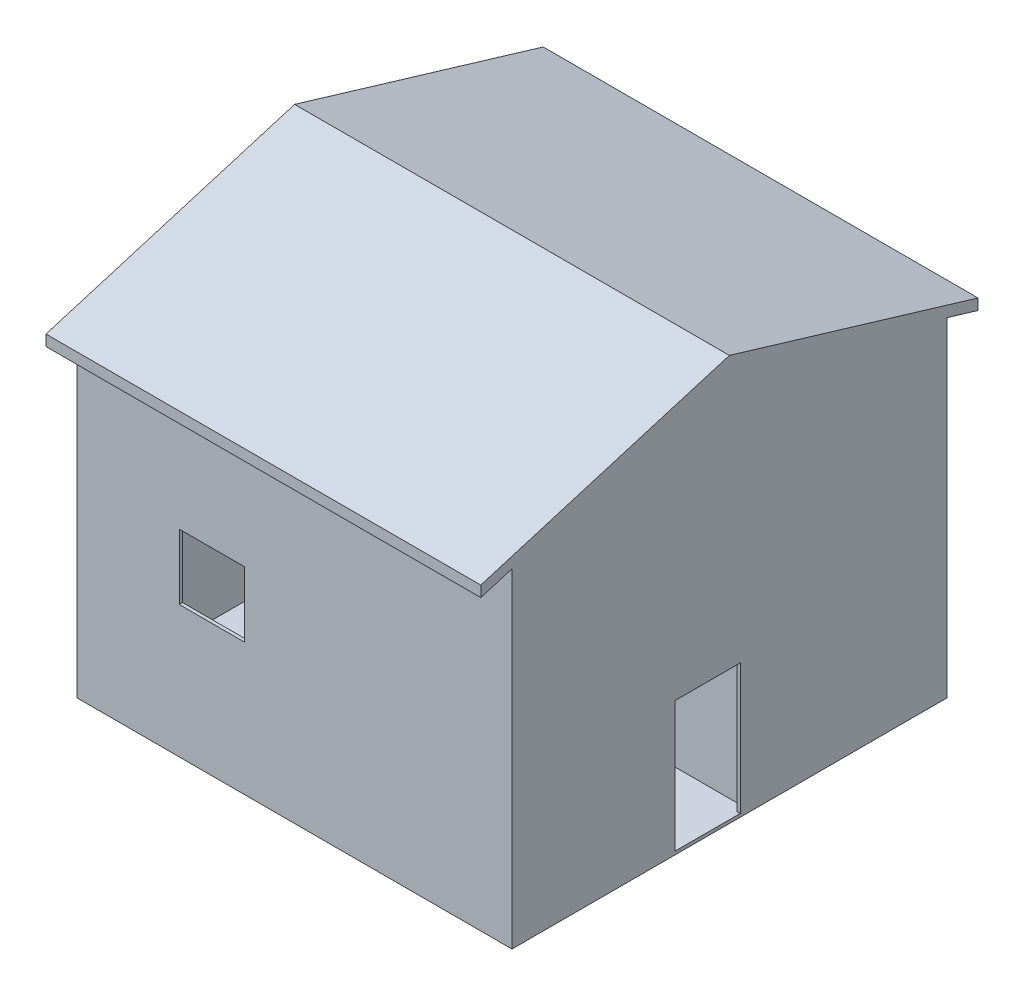
SolidWorks part; units mm, degrees
material "純金"
ref_plane "前基準面" through (0, 0, 0) normal (0, 0, 1) x (1, 0, 0)
ref_plane "上基準面" through (0, 0, 0) normal (0, 1, 0) x (1, 0, 0)
ref_plane "右基準面" through (0, 0, 0) normal (1, 0, 0) x (0, 0, -1)
ref_plane "平面1" through (98.5, 0, 0) normal (-1, 0, 0) x (0, -1, 0)
sketch "草圖1" plane through (98.5, 0, 0) normal (-1, 0, 0) x (0, -1, 0)
  line L0 (-1.5, -5) -> (-151.5, -5)
  line L1 (-151.5, -5) -> (-151.5, -8.5)
  line L2 (-151.5, -8.5) -> (-1.5, -8.5)
  line L3 (-1.5, -8.5) -> (-1.5, -5)
extrude "填料-伸長1" add sketch "草圖1" against normal blind 1.5
sketch "草圖2" plane through (0, 0, -8.5) normal (0, 0, -1) x (-1, 0, 0)
  line L0 (21.1717, 1.5) -> (-100, 1.5)
  line L1 (-100, 1.5) -> (-100, 151.5)
  line L2 (-100, 151.5) -> (21.1717, 151.5)
  line L3 (21.1717, 151.5) -> (21.1717, 1.5)
extrude "填料-伸長2" add sketch "草圖2" along normal blind 91.5
sketch "草圖3" plane through (0, 0, -5) normal (0, 0, 1) x (1, 0, 0)
  line L0 (98.5, 61.5) -> (98.5, 151.5)
  line L1 (98.5, 151.5) -> (100, 151.5)
  line L2 (100, 151.5) -> (100, 61.5)
  line L3 (100, 61.5) -> (98.5, 61.5)
extrude "填料-伸長3" add sketch "草圖3" along normal blind 30
sketch "草圖4" plane through (-21.1717, 0, 0) normal (-1, 0, 0) x (0, 0, 1)
  line L0 (-100, 1.5) -> (-100, 151.5)
  line L1 (-100, 151.5) -> (-8.5, 151.5)
  line L2 (-8.5, 151.5) -> (-8.5, 61.5)
  line L3 (-8.5, 61.5) -> (-10, 61.5)
  line L4 (-10, 61.5) -> (-10, 1.5)
  line L5 (-10, 1.5) -> (-100, 1.5)
extrude "填料-伸長4" add sketch "草圖4" along normal blind 30
sketch "草圖5" plane through (0, 1.5, 0) normal (0, -1, 0) x (1, 0, 0)
  line L0 (-51.1717, 25) -> (100, 25)
  line L1 (100, 25) -> (100, -100)
  line L2 (100, -100) -> (-51.1717, -100)
  line L3 (-51.1717, -100) -> (-51.1717, 25)
extrude "填料-伸長5" add sketch "草圖5" along normal blind 1.5
sketch "草圖6" plane through (-51.1717, 0, 0) normal (-1, 0, 0) x (0, 0, 1)
  line L0 (25, 0) -> (-100, 0)
  line L1 (-100, 0) -> (-100, 151.5)
  line L2 (-100, 151.5) -> (25, 151.5)
  line L3 (25, 151.5) -> (25, 0)
extrude "填料-伸長6" add sketch "草圖6" along normal blind 48.8283
sketch "草圖7" plane through (0, 0, 25) normal (0, 0, 1) x (1, 0, 0)
  line L0 (100, 0) -> (-100, 0)
  line L1 (-100, 0) -> (-100, 151.5)
  line L2 (-100, 151.5) -> (100, 151.5)
  line L3 (100, 151.5) -> (100, 0)
extrude "填料-伸長7" add sketch "草圖7" along normal blind 75
sketch "草圖8" plane through (0, 0, 25) normal (0, 0, -1) x (-1, 0, 0)
  line L0 (-23.5, 151.5) -> (-23.5, 1.5)
  line L1 (-23.5, 1.5) -> (51.1717, 1.5)
  line L2 (51.1717, 1.5) -> (51.1717, 151.5)
  line L3 (51.1717, 151.5) -> (-23.5, 151.5)
extrude "除料-伸長1" cut sketch "草圖8" against normal blind 53.5
sketch "草圖9" plane through (0, 0, -10) normal (0, 0, 1) x (1, 0, 0)
  line L0 (-21.1717, 1.5) -> (-21.1717, 151.5)
  line L1 (-21.1717, 151.5) -> (-51.1717, 151.5)
  line L2 (-51.1717, 151.5) -> (-51.1717, 1.5)
  line L3 (-51.1717, 1.5) -> (-21.1717, 1.5)
extrude "除料-伸長2" cut sketch "草圖9" against normal blind 59.25
sketch "草圖10" plane through (-21.1717, 0, 0) normal (-1, 0, 0) x (0, 0, 1)
  line L0 (-69.25, 151.5) -> (-69.25, 1.5)
  line L1 (-69.25, 1.5) -> (-10, 1.5)
  line L2 (-10, 1.5) -> (-10, 151.5)
  line L3 (-10, 151.5) -> (-69.25, 151.5)
extrude "除料-伸長3" cut sketch "草圖10" against normal blind 42.6717
sketch "草圖11" plane through (23.5, 0, 0) normal (-1, 0, 0) x (0, 0, 1)
  line L0 (78.5, 61.5) -> (48.5, 61.5)
  line L1 (48.5, 61.5) -> (48.5, 1.5)
  line L2 (48.5, 1.5) -> (78.5, 1.5)
  line L3 (78.5, 1.5) -> (78.5, 61.5)
extrude "除料-伸長4" cut sketch "草圖11" against normal blind 1.5
sketch "草圖12" plane through (21.5, 0, 0) normal (-1, 0, 0) x (0, 0, 1)
  line L0 (-69.25, 61.5) -> (-69.25, 1.5)
  line L1 (-69.25, 1.5) -> (-39.25, 1.5)
  line L2 (-39.25, 1.5) -> (-39.25, 61.5)
  line L3 (-39.25, 61.5) -> (-69.25, 61.5)
extrude "除料-伸長5" cut sketch "草圖12" against normal blind 1.5
sketch "草圖13" plane through (-51.1717, 0, 0) normal (1, 0, 0) x (0, 0, -1)
  line L0 (-78.5, 151.5) -> (-78.5, 1.5)
  line L1 (-78.5, 1.5) -> (8.5, 1.5)
  line L2 (8.5, 1.5) -> (8.5, 151.5)
  line L3 (8.5, 151.5) -> (-78.5, 151.5)
extrude "除料-伸長6" cut sketch "草圖13" against normal blind 47.3283
sketch "草圖14" plane through (-51.1717, 0, 0) normal (1, 0, 0) x (0, 0, -1)
  line L0 (69.25, 1.5) -> (69.25, 151.5)
  line L1 (69.25, 151.5) -> (10, 151.5)
  line L2 (10, 151.5) -> (10, 1.5)
  line L3 (10, 1.5) -> (69.25, 1.5)
extrude "除料-伸長7" cut sketch "草圖14" against normal blind 47.3283
sketch "草圖15" plane through (0, 0, -69.25) normal (0, 0, 1) x (1, 0, 0)
  line L0 (-98.5, 1.5) -> (21.5, 1.5)
  line L1 (21.5, 1.5) -> (21.5, 151.5)
  line L2 (21.5, 151.5) -> (-98.5, 151.5)
  line L3 (-98.5, 151.5) -> (-98.5, 1.5)
extrude "除料-伸長8" cut sketch "草圖15" against normal blind 29.25
sketch "草圖16" plane through (23, 0, 0) normal (-1, 0, 0) x (0, 0, 1)
  line L0 (-98.5, 1.5) -> (-10, 1.5)
  line L1 (-10, 1.5) -> (-10, 151.5)
  line L2 (-10, 151.5) -> (-98.5, 151.5)
  line L3 (-98.5, 151.5) -> (-98.5, 1.5)
extrude "除料-伸長9" cut sketch "草圖16" against normal blind 75.5
sketch "草圖17" plane through (0, 0, 78.5) normal (0, 0, -1) x (-1, 0, 0)
  line L0 (98.5, 151.5) -> (-23.5, 151.5)
  line L1 (-23.5, 151.5) -> (-23.5, 1.5)
  line L2 (-23.5, 1.5) -> (98.5, 1.5)
  line L3 (98.5, 1.5) -> (98.5, 151.5)
extrude "除料-伸長10" cut sketch "草圖17" against normal blind 20
sketch "草圖18" plane through (25, 0, 0) normal (-1, 0, 0) x (0, 0, 1)
  line L0 (98.5, 151.5) -> (48.5, 151.5)
  line L1 (48.5, 151.5) -> (48.5, 1.5)
  line L2 (48.5, 1.5) -> (98.5, 1.5)
  line L3 (98.5, 1.5) -> (98.5, 151.5)
extrude "除料-伸長11" cut sketch "草圖18" against normal blind 73.5
sketch "草圖19" plane through (0, 0, 48.5) normal (0, 0, 1) x (1, 0, 0)
  line L0 (25, 1.5) -> (98.5, 1.5)
  line L1 (98.5, 1.5) -> (98.5, 151.5)
  line L2 (98.5, 151.5) -> (25, 151.5)
  line L3 (25, 151.5) -> (25, 1.5)
extrude "除料-伸長12" cut sketch "草圖19" against normal blind 18.5
sketch "草圖20" plane through (0, 0, 25) normal (0, 0, -1) x (-1, 0, 0)
  line L0 (-98.5, 1.5) -> (-23.5, 1.5)
  line L1 (-23.5, 1.5) -> (-23.5, 151.5)
  line L2 (-23.5, 151.5) -> (-98.5, 151.5)
  line L3 (-98.5, 151.5) -> (-98.5, 1.5)
extrude "除料-伸長13" cut sketch "草圖20" against normal blind 3.5
sketch "草圖21" plane through (0, 0, -100) normal (0, 0, -1) x (-1, 0, 0)
  line L0 (-67.804, 45.1558) -> (-37.804, 45.1558)
  line L1 (-37.804, 45.1558) -> (-37.804, 75.1558)
  line L2 (-37.804, 75.1558) -> (-67.804, 75.1558)
  line L3 (-67.804, 75.1558) -> (-67.804, 45.1558)
extrude "除料-伸長14" cut sketch "草圖21" against normal up to next
sketch "草圖22" plane through (0, 0, -100) normal (0, 0, -1) x (-1, 0, 0)
  line L0 (51.2266, 45.5945) -> (51.2266, 75.5945)
  line L1 (51.2266, 75.5945) -> (21.2266, 75.5945)
  line L2 (21.2266, 75.5945) -> (21.2266, 45.5945)
  line L3 (21.2266, 45.5945) -> (51.2266, 45.5945)
extrude "除料-伸長15" cut sketch "草圖22" against normal up to next
sketch "草圖23" plane through (0, 0, 100) normal (0, 0, 1) x (1, 0, 0)
  line L0 (-53.0614, 60.75) -> (-23.0614, 60.75)
  line L1 (-23.0614, 60.75) -> (-23.0614, 90.75)
  line L2 (-23.0614, 90.75) -> (-53.0614, 90.75)
  line L3 (-53.0614, 90.75) -> (-53.0614, 60.75)
extrude "除料-伸長16" cut sketch "草圖23" against normal up to next
sketch "草圖24" plane through (0, 1.5, 0) normal (0, 1, 0) x (1, 0, 0)
  line L1 (98.5, 8.5) -> (98.5, 5) construction
  line L3 (100, 5) -> (98.5, 5) construction
  circle A0 centre (98, 4.5) radius 0.5
  dimension "D1" = 1
sketch "草圖26" plane through (100, 0, 0) normal (1, 0, 0) x (0, 0, -1)
  line L0 (0, 151.5) -> (0, 181.5) construction
  line L1 (-100, 151.5) -> (100, 151.5) construction
  line L2 (0, 181.5) -> (-100, 151.5)
  line L3 (-100, 151.5) -> (-114.3674, 147.1898)
  line L4 (0, 181.5) -> (100, 151.5)
  line L5 (100, 151.5) -> (114.3674, 147.1898)
  line L6 (0, 186.5) -> (-114.3674, 152.1898)
  line L7 (0, 186.5) -> (114.3674, 152.1898)
  line L8 (114.3674, 147.1898) -> (114.3674, 152.1898)
  line L9 (-114.3674, 147.1898) -> (-114.3674, 152.1898)
  line L10 (-100, 151.5) -> (0, 151.5)
  line L11 (-100, 151.5) -> (100, 151.5)
  line L12 (0, 151.5) -> (-100, 151.5)
  line L13 (0, 151.5) -> (100, 151.5)
extrude "填料-伸長11" add sketch "草圖26" against normal blind 200 separate body contours L9 L3 L2 L4 L5 L8 L7 L6 | L11
sketch "草圖27" plane through (100, 0, 0) normal (1, 0, 0) x (0, 0, -1)
  line L0 (0, 151.5) -> (0, 181.5) construction
  line L1 (-100, 151.5) -> (100, 151.5) construction
  line L2 (0, 181.5) -> (-100, 151.5)
  line L3 (-100, 151.5) -> (0, 151.5)
  line L4 (0, 151.5) -> (100, 151.5)
  line L5 (100, 151.5) -> (0, 181.5)
extrude "填料-伸長12" add sketch "草圖27" against normal blind 200
